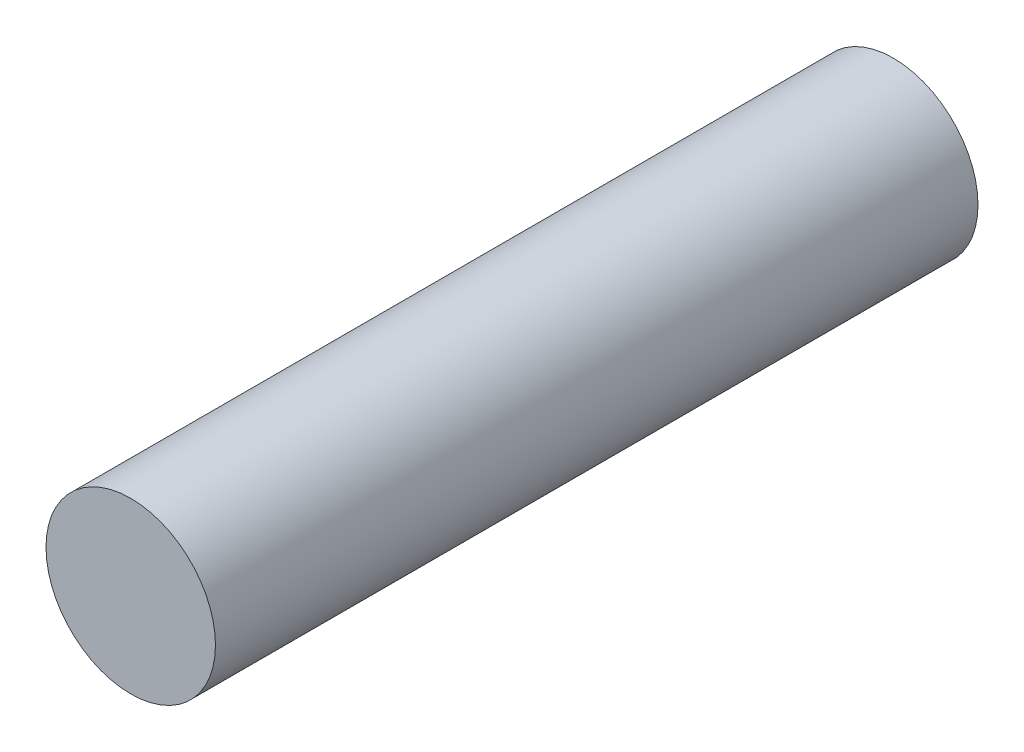
SolidWorks part; units mm, degrees
ref_plane "Front Plane" through (0, 0, 0) normal (0, 0, 1) x (1, 0, 0)
ref_plane "Top Plane" through (0, 0, 0) normal (0, 1, 0) x (1, 0, 0)
ref_plane "Right Plane" through (0, 0, 0) normal (1, 0, 0) x (0, 0, -1)
sketch "Sketch1" plane through (0, 0, 0) normal (0, 0, 1) x (1, 0, 0)
  circle A0 centre (0, 0) radius 1
  dimension "D1" = 2
extrude "Boss-Extrude1" add sketch "Sketch1" along normal mid plane 9 contours A0
